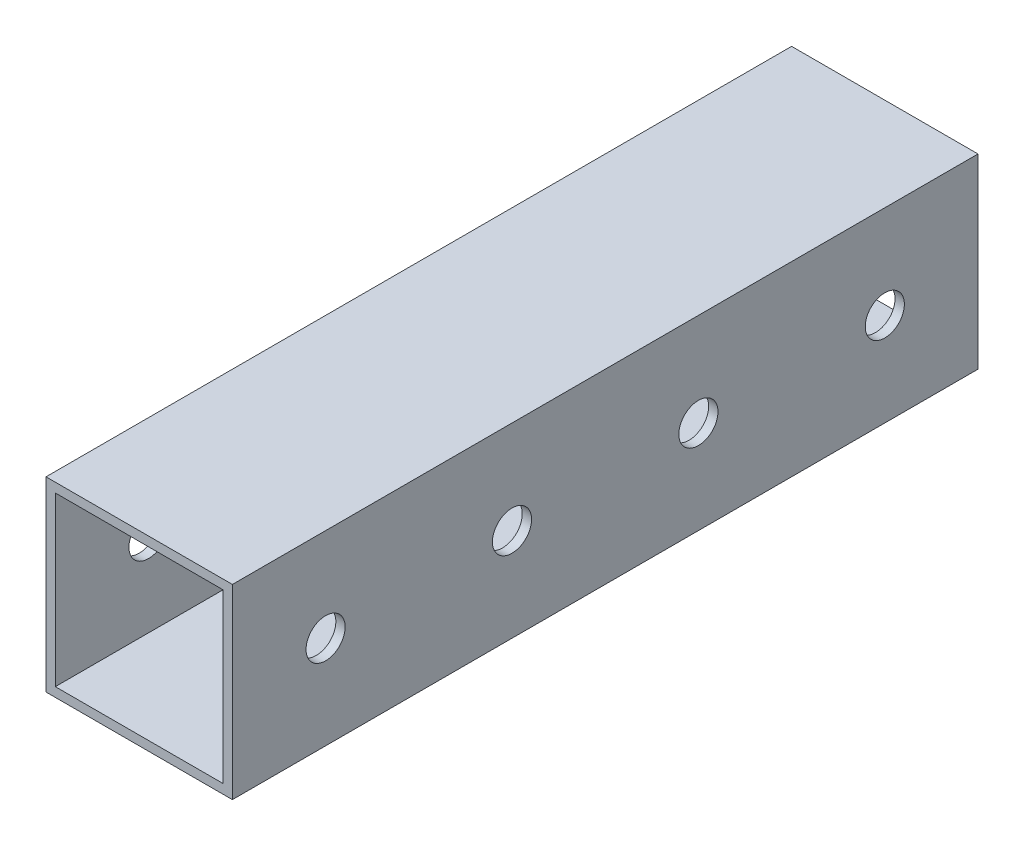
SolidWorks part; units mm, degrees
ref_plane "前视基准面" through (0, 0, 0) normal (0, 0, 1) x (1, 0, 0)
ref_plane "上视基准面" through (0, 0, 0) normal (0, 1, 0) x (1, 0, 0)
ref_plane "右视基准面" through (0, 0, 0) normal (1, 0, 0) x (0, 0, -1)
sketch "草图1" plane through (0, 0, 0) normal (0, 0, 1) x (1, 0, 0)
  line L1 (-10, 10) -> (10, 10)
  line L2 (-10, 10) -> (-10, -10)
  line L3 (-10, -10) -> (10, -10)
  line L4 (10, 10) -> (10, -10)
  line L5 (-10, 10) -> (10, -10) construction
  line L6 (-10, -10) -> (10, 10) construction
  point P0 (0, 0)
  dimension "D1" = 20
  dimension "D2" = 20
extrude "凸台-拉伸1" add sketch "草图1" along normal blind 80
sketch "草图2" plane through (10, 0, 0) normal (1, 0, 0) x (0, 0, -1)
  line L0 (-40, 10) -> (-40, -10)
  line L1 (-80, 10) -> (0, 10) construction
  line L2 (-80, -10) -> (0, -10) construction
  line L3 (-80, -10) -> (-80, 10) construction
  circle A0 centre (-70, 0) radius 2.1
  circle A1 centre (-50, 0) radius 2.1
  circle A2 centre (-30, 0) radius 2.1
  circle A3 centre (-10, 0) radius 2.1
  dimension "D1" = 10
  dimension "D3" = 4.2
  dimension "D2" = 10
  dimension "D5" = 20
  dimension "D4" = 2
extrude "切除-拉伸1" cut sketch "草图2" against normal through all contours A0 | A3 | A1 | A2
sketch "草图3" plane through (0, 0, 0) normal (0, 0, -1) x (-1, 0, 0)
  line L1 (-9, 9) -> (9, 9)
  line L2 (-9, 9) -> (-9, -9)
  line L3 (-9, -9) -> (9, -9)
  line L4 (9, 9) -> (9, -9)
  line L5 (-9, 9) -> (9, -9) construction
  line L6 (-9, -9) -> (9, 9) construction
  point P0 (0, 0)
  dimension "D1" = 18
  dimension "D2" = 18
extrude "切除-拉伸2" cut sketch "草图3" against normal through all
